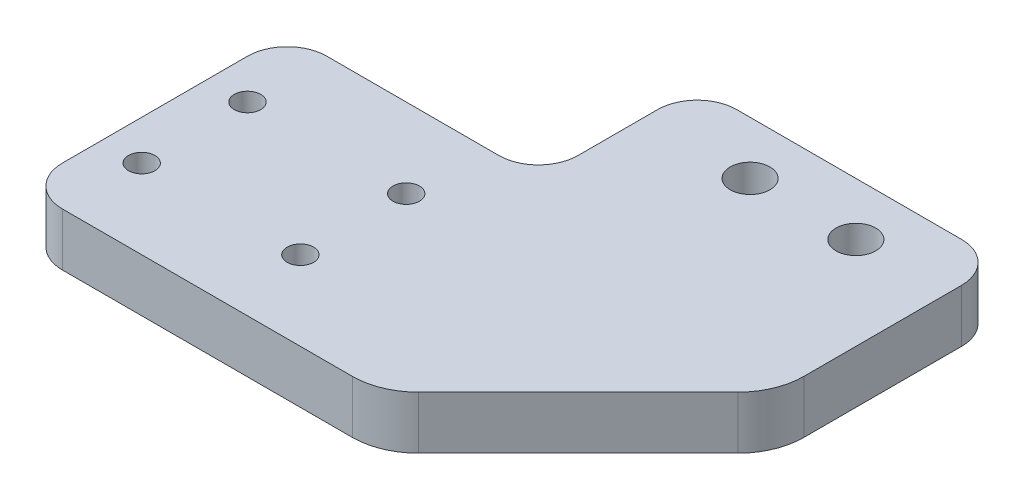
SolidWorks part; units mm, degrees
material "Thornel Mat VMA"
ref_plane "前视基准面" through (0, 0, 0) normal (0, 0, 1) x (1, 0, 0)
ref_plane "上视基准面" through (0, 0, 0) normal (0, 1, 0) x (1, 0, 0)
ref_plane "右视基准面" through (0, 0, 0) normal (1, 0, 0) x (0, 0, -1)
other "Configuration Table"
sketch "草图1" plane through (0, 0, 0) normal (0, 1, 0) x (1, 0, 0)
  line L0 (0, 0) -> (0, 20.1669) construction
  line L1 (-40, -10) -> (40, -10)
  line L2 (-40, -10) -> (-40, 10)
  line L3 (-40, 10) -> (40, 10)
  line L4 (40, -10) -> (40, 10)
  line L5 (-40, -10) -> (40, 10) construction
  line L6 (-40, 10) -> (40, -10) construction
  line L7 (0, 0) -> (39.3199, 0) construction
  line L8 (0, 0) -> (0, 19.4616) construction
  line L9 (30, 0) -> (30, 22.3006) construction
  line L10 (40, 10) -> (63, 10)
  line L11 (63, 10) -> (63, -10)
  line L12 (63, -10) -> (40, -10)
  line L13 (40, 10) -> (40, 22)
  line L14 (40, 22) -> (63, 22)
  line L15 (63, 22) -> (63, 10)
  line L16 (21, 10) -> (21, -10)
  circle A0 centre (-4, 6) radius 1
  circle A1 centre (4, 6) radius 1
  circle A2 centre (4, -6) radius 1
  circle A3 centre (-4, -6) radius 1
  circle A4 centre (24, 4) radius 1
  circle A5 centre (36, 4) radius 1
  circle A6 centre (36, -4) radius 1
  circle A7 centre (24, -4) radius 1
  circle A8 centre (-24, -4) radius 1
  circle A9 centre (-36, -4) radius 1
  circle A10 centre (-36, 4) radius 1
  circle A11 centre (-24, 4) radius 1
  circle A22 centre (48, 18) radius 1.5
  circle A23 centre (56, 18) radius 1.5
  point P0 (0, 0)
  dimension "D3" = 2
  dimension "D4" = 8
  dimension "D5" = 12
  dimension "D7" = 2
  dimension "D8" = 12
  dimension "D9" = 8
  dimension "D14" = 12
  dimension "D15" = 3
  dimension "D16" = 3
  dimension "D17" = 8
  dimension "D18" = 4
  dimension "D19" = 4
  dimension "D20" = 7
  dimension "D1" = 80
  dimension "D2" = 20
  dimension "D6" = 0
  dimension "D10" = 30
  dimension "D11" = 23
  dimension "D21" = 19
extrude "凸台-拉伸1" add sketch "草图1" along normal blind 4
fillet "圆角1" radius 3 5 edges at (63, 2, -22) (40, 2, -22) (40, 2, -10) (21, 2, 10) (21, 2, -10)
chamfer "倒角1" distance 15 angle 45 1 edges at (63, 2, 10)
fillet "圆角2" radius 5 2 edges at (63, 2, -5) (48, 2, 10)
